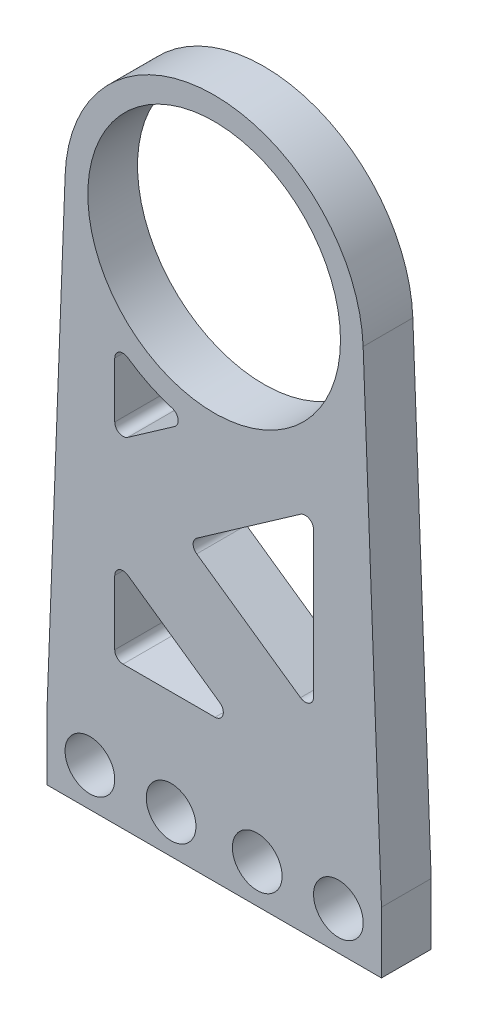
SolidWorks part; units mm, degrees
material "Foam"
ref_plane "Front Plane" through (0, 0, 0) normal (0, 0, 1) x (1, 0, 0)
ref_plane "Top Plane" through (0, 0, 0) normal (0, 1, 0) x (1, 0, 0)
ref_plane "Right Plane" through (0, 0, 0) normal (1, 0, 0) x (0, 0, -1)
sketch "Sketch1" plane through (0, 0, 0) normal (0, 0, 1) x (1, 0, 0)
  line L0 (-11.1, 83.4741) -> (-9.1, 83.4741)
  line L1 (0, 41.6741) -> (20.2, 41.6741) construction
  line L2 (20.2, 41.6741) -> (20.2, 83.4741) construction
  line L3 (0, 83.4741) -> (9.1, 83.4741)
  line L4 (10.1, 83.4741) -> (10.1, 41.6741) construction
  line L5 (0, 62.5741) -> (20.2, 62.5741) construction
  line L6 (-20.2, 83.4741) -> (-20.2, 41.6741) construction
  line L7 (-20.2, 41.6741) -> (0, 41.6741) construction
  line L8 (-20.2, 83.4741) -> (-11.1, 83.4741)
  line L9 (-10.1, 83.4741) -> (-10.1, 41.6741) construction
  line L10 (-20.2, 62.5741) -> (0, 62.5741) construction
  line L11 (-20.2, 41.6741) -> (-17.9755, -0.9384) construction
  line L12 (20.2, 41.6741) -> (17.9755, -0.9384) construction
  line L13 (0, 0) -> (0, 147.6909) construction
  line L14 (-20.2, 90.8741) -> (-17.9867, 148.3831)
  line L15 (20.2, 90.8741) -> (17.9867, 148.3831)
  line L16 (11.1, 83.4741) -> (20.2, 83.4741)
  line L17 (-11.1, 83.4741) -> (-11.1, 89.4741) construction
  line L18 (-11.1, 89.4741) -> (-9.1, 89.4741) construction
  line L19 (-9.1, 83.4741) -> (-9.1, 89.4741) construction
  line L20 (11.1, 83.4741) -> (9.1, 83.4741)
  line L21 (11.1, 83.4741) -> (11.1, 89.4741) construction
  line L22 (11.1, 89.4741) -> (9.1, 89.4741) construction
  line L23 (9.1, 83.4741) -> (9.1, 89.4741) construction
  line L24 (-9.1, 83.4741) -> (0, 83.4741)
  line L25 (-20.2, 90.8741) -> (20.2, 90.8741) construction
  line L26 (-20.2, 83.4741) -> (-20.2, 90.8741)
  line L27 (20.2, 83.4741) -> (20.2, 90.8741)
  circle A0 centre (10.1, 73.3741) radius 6.5 construction
  arc A1 (-17.9755, -0.9384) -> (17.9755, -0.9384) centre (0, 0) cw construction
  circle A2 centre (0, 0) radius 2.5 construction
  arc A3 (-17.9755, -0.9384) -> (17.9755, -0.9384) centre (0, 0) ccw construction
  circle A4 centre (5.2, 88.1241) radius 3
  circle A5 centre (15, 88.1241) radius 3
  circle A6 centre (-10.1, 51.7741) radius 6.5 construction
  circle A7 centre (-15, 88.1241) radius 3
  circle A8 centre (-5.2, 88.1241) radius 3
  circle A9 centre (-15, 37.0241) radius 3 construction
  circle A10 centre (-5.2, 37.0241) radius 3 construction
  circle A11 centre (0, 0) radius 52.75 construction
  circle A12 centre (5.2, 37.0241) radius 3 construction
  circle A13 centre (15, 37.0241) radius 3 construction
  arc A14 (17.9867, 148.3831) -> (-17.9867, 148.3831) centre (0, 147.6909) ccw
  circle A15 centre (0, 147.6909) radius 7.95
  circle A16 centre (10.1, 73.3741) radius 75 construction
  dimension "D1" = 5
  dimension "D2" = 18
  dimension "D10" = 51.1
  dimension "D3" = 13
  dimension "D4" = 6
  dimension "D8" = 9.8
  dimension "D9" = 105.5
  dimension "D5" = 20.2
  dimension "D19" = 36
  dimension "D20" = 15.9
  dimension "D18" = 150
  dimension "D6" = 10.1
  dimension "D7" = 41.8
  dimension "D13" = 10.1
  dimension "D14" = 6
  dimension "D15" = 9.8
  dimension "D16" = 2
  dimension "D21" = 7.4
extrude "Main Body Link B1" add sketch "Sketch1" along normal blind 6
sketch "Sketch2" plane through (0, 0, 6) normal (0, 0, 1) x (1, 0, 0)
  line L0 (0, 147.6909) -> (0, 83.4741) construction
  line L1 (-12, 134.2745) -> (12, 134.2745) construction
  line L2 (-12, 134.2745) -> (-12, 123.585)
  line L3 (-12, 100.6909) -> (3.2782, 100.6909)
  line L4 (12, 128.1722) -> (12, 106.7932)
  line L5 (-12, 117.4827) -> (12, 117.4827) construction
  line L6 (-12, 111.3804) -> (-12, 100.6909)
  line L7 (12, 100.6909) -> (-12, 117.4827) construction
  line L8 (-12, 117.4827) -> (12, 134.2745) construction
  line L9 (3.2782, 100.6909) -> (-12, 111.3804)
  line L10 (-12, 123.585) -> (-2.9299, 129.9309)
  line L12 (-3.2782, 117.4827) -> (12, 106.7932)
  line L13 (-3.2782, 117.4827) -> (12, 128.1722)
  line L14 (3.2782, 100.6909) -> (12, 100.6909) construction
  line L15 (12, 100.6909) -> (12, 106.7932) construction
  line L16 (-12, 123.585) -> (-12, 117.4827) construction
  line L17 (-12, 117.4827) -> (-12, 111.3804) construction
  line L19 (12, 134.2745) -> (12, 128.1722) construction
  line L20 (-20.2, 83.4741) -> (20.2, 83.4741) construction
  arc A0 (-12, 134.2745) -> (-2.9299, 129.9309) centre (0, 147.6909) ccw
  arc A1 (-17.9867, 148.3831) -> (-12, 134.2745) centre (0, 147.6909) ccw construction
  arc A2 (12, 134.2745) -> (17.9867, 148.3831) centre (0, 147.6909) ccw construction
  arc A3 (17.9867, 148.3831) -> (-17.9867, 148.3831) centre (0, 147.6909) ccw construction
  dimension "D1" = 24
  dimension "D2" = 47
  dimension "D4" = 10
extrude "Cut-Extrude1" cut sketch "Sketch2" against normal up to next contours L13 L12 L4 | A0 L2 L10 | L6 L3 L9
sketch "Sketch3" plane through (0, 0, 6) normal (0, 0, 1) x (1, 0, 0)
  line L0 (0, 147.6909) -> (0, 139.7409) construction
  circle A0 centre (-11.5, 147.6909) radius 1.5
  circle A1 centre (11.5, 147.6909) radius 1.5
  circle A2 centre (0, 147.6909) radius 7.95 construction
  dimension "D1" = 3
  dimension "D2" = 11.5
extrude "Cut-Extrude2" cut sketch "Sketch3" against normal up to next
fillet "Fillet1" radius 1 9 edges at (-12, 100.6909, 3) (3.2782, 100.6909, 3) (-12, 111.3804, 3) (12, 106.7932, 3) (12, 128.1722, 3) (-3.2782, 117.4827, 3) (-12, 123.585, 3) (-2.9299, 129.9309, 3) (-12, 134.2745, 3)
sketch "Sketch4" plane through (0, 0, 6) normal (0, 0, 1) x (1, 0, 0)
  circle A0 centre (0, 147.6909) radius 15.25
  dimension "D1" = 30.5
extrude "Cut-Extrude3" cut sketch "Sketch4" against normal through all
equation "\"D20@Sketch1\"=16.00mm-+\"radii_fit@Parameters@Parameters.SLDPRT\""
equation "\"D9@Sketch1\"=\"CenterDist2@Parameters@Parameters.SLDPRT\"*2"
equation "\"D18@Sketch1\"=\"CenterDist3@Parameters@Parameters.SLDPRT\"*2"
